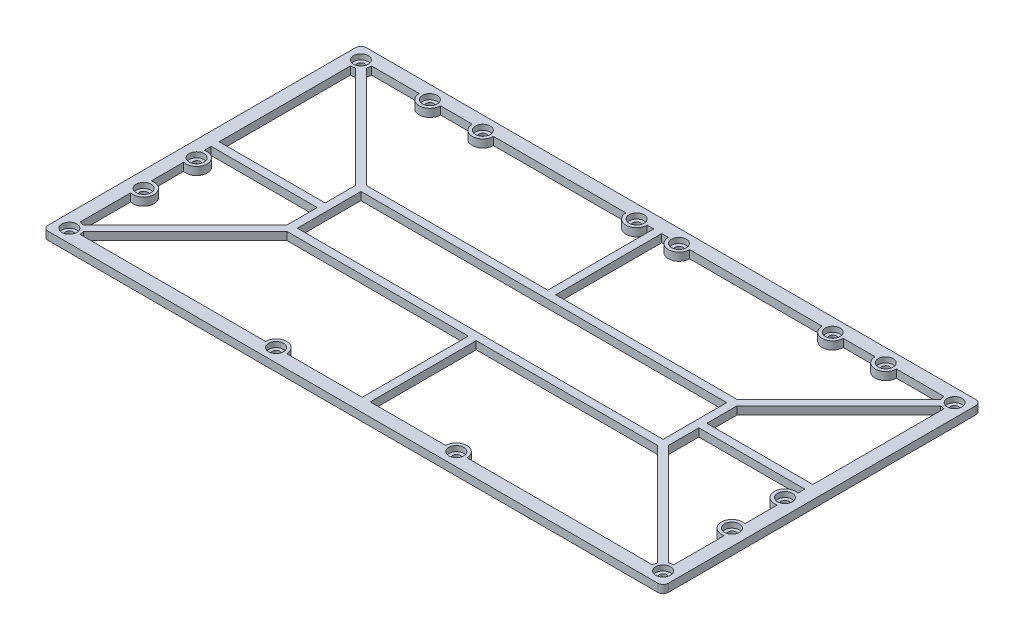
SolidWorks part; units mm, degrees
ref_plane "前视基准面" through (0, 0, 0) normal (0, 0, 1) x (1, 0, 0)
ref_plane "上视基准面" through (0, 0, 0) normal (0, 1, 0) x (1, 0, 0)
ref_plane "右视基准面" through (0, 0, 0) normal (1, 0, 0) x (0, 0, -1)
sketch "草图1" plane through (0, 0, 0) normal (0, 1, 0) x (1, 0, 0)
  line L0 (-13.5, 0) -> (0, 0) construction
  line L1 (-117, 60) -> (117, 60)
  line L2 (-117, 60) -> (-117, -60)
  line L3 (-117, -60) -> (117, -60)
  line L4 (117, 60) -> (117, -60)
  line L5 (-117, 60) -> (117, -60) construction
  line L6 (-117, -60) -> (117, 60) construction
  line L7 (0, 0) -> (0, 78.7988) construction
  circle A0 centre (-58.5, 0) radius 45
  circle A1 centre (58.5, 0) radius 45
  point P0 (0, 0)
  dimension "D3" = 90
  dimension "D4" = 13.5
  dimension "D1" = 234
  dimension "D2" = 120
extrude "凸台-拉伸1" add sketch "草图1" along normal blind 3
sketch "草图2" plane through (0, 3, 0) normal (0, 1, 0) x (1, 0, 0)
  line L0 (-58.5, 0) -> (-58.5, 18.4943) construction
  line L1 (0, 0) -> (0, 13.9098) construction
  circle A8 centre (-58.5, 0) radius 50 construction
  circle A9 centre (-88.5, -40) radius 1.5
  circle A10 centre (-83.5, 43.3013) radius 1.5
  circle A11 centre (-33.5, 43.3013) radius 1.5
  circle A12 centre (-28.5, -40) radius 1.5
  circle A13 centre (28.5, -40) radius 1.5
  circle A14 centre (88.5, -40) radius 1.5
  circle A15 centre (33.5, 43.3013) radius 1.5
  circle A16 centre (83.5, 43.3013) radius 1.5
  dimension "D1" = 100
  dimension "D3" = 30
  dimension "D2" = 3
  dimension "D4" = 25
  dimension "D5" = 3
extrude "切除-拉伸1" cut sketch "草图2" against normal blind 3
sketch "草图3" plane through (0, 3, 0) normal (0, 1, 0) x (1, 0, 0)
  line L0 (-117, 60) -> (-117, -60) construction
  line L1 (-117, -60) -> (117, -60) construction
  line L2 (0, 0) -> (0, -72.8657) construction
  line L3 (117, 60) -> (-117, 60) construction
  circle A0 centre (-111, -28) radius 1.5
  circle A1 centre (-111, -8) radius 1.5
  circle A2 centre (111, -8) radius 1.5
  circle A3 centre (111, -28) radius 1.5
  circle A4 centre (-86, 55) radius 1.5
  circle A5 centre (-66, 55) radius 1.5
  circle A6 centre (66, 55) radius 1.5
  circle A7 centre (86, 55) radius 1.5
  dimension "D1" = 3
  dimension "D2" = 6
  dimension "D3" = 32
  dimension "D4" = 3
  dimension "D5" = 20
  dimension "D6" = 3
  dimension "D7" = 5
  dimension "D8" = 31
  dimension "D9" = 3
  dimension "D10" = 20
extrude "切除-拉伸2" cut sketch "草图3" against normal blind 3
sketch "草图4" plane through (0, 3, 0) normal (0, 1, 0) x (1, 0, 0)
  line L0 (-117, 60) -> (-117, -60) construction
  line L1 (-117, -60) -> (117, -60) construction
  line L2 (117, 60) -> (-117, 60) construction
  line L3 (117, -60) -> (117, 60) construction
  circle A0 centre (-112, -55) radius 1.5
  circle A1 centre (-112, 55) radius 1.5
  circle A2 centre (112, 55) radius 1.5
  circle A3 centre (112, -55) radius 1.5
  circle A4 centre (-34, -55) radius 1.5
  circle A5 centre (34, -55) radius 1.5
  dimension "D1" = 3
  dimension "D2" = 5
  dimension "D3" = 5
  dimension "D4" = 3
  dimension "D5" = 5
  dimension "D6" = 5
  dimension "D7" = 3
  dimension "D8" = 5
  dimension "D9" = 5
  dimension "D10" = 3
  dimension "D11" = 3
  dimension "D12" = 78
  dimension "D13" = 3
  dimension "D14" = 78
  dimension "D15" = 5
  dimension "D16" = 5
  dimension "D17" = 5
  dimension "D18" = 5
extrude "切除-拉伸3" cut sketch "草图4" against normal blind 3
sketch "草图5" plane through (0, 3, 0) normal (0, 1, 0) x (1, 0, 0)
  line L0 (117, 60) -> (-117, 60) construction
  circle A0 centre (-8, 55) radius 1.5
  circle A1 centre (8, 55) radius 1.5
  dimension "D1" = 3
  dimension "D2" = 5
  dimension "D3" = 8
  dimension "D4" = 3
  dimension "D5" = 5
  dimension "D6" = 8
extrude "切除-拉伸4" cut sketch "草图5" against normal blind 3
fillet "圆角1" radius 2 4 edges at (-117, 1.5, -60) (-117, 1.5, 60) (117, 1.5, 60) (117, 1.5, -60)
sketch "草图6" plane through (0, 3, 0) normal (0, 1, 0) x (1, 0, 0)
  line L5 (109.5, -12.7697) -> (109.5, -23.2303)
  line L6 (-107.6699, 52.5) -> (-90.3301, 52.5)
  line L7 (-109.5, 50.6699) -> (-109.5, -3.2303)
  line L12 (-107.6699, -52.5) -> (-38.3301, -52.5)
  line L13 (109.5, 50.6699) -> (109.5, -3.2303)
  line L14 (-108.1247, 51.8406) -> (108.1247, -51.8406) construction
  line L15 (-108.1247, -51.8406) -> (108.1247, 51.8406) construction
  line L16 (109.5, -32.7697) -> (109.5, -50.6699)
  line L17 (90.3301, 52.5) -> (107.6699, 52.5)
  line L18 (70.3301, 52.5) -> (81.6699, 52.5)
  line L19 (12.3301, 52.5) -> (61.6699, 52.5)
  line L20 (-3.6699, 52.5) -> (3.6699, 52.5)
  line L21 (-81.6699, 52.5) -> (-70.3301, 52.5)
  line L22 (-61.6699, 52.5) -> (-12.3301, 52.5)
  line L23 (-109.5, -12.7697) -> (-109.5, -23.2303)
  line L24 (-109.5, -32.7697) -> (-109.5, -50.6699)
  line L25 (-29.6699, -52.5) -> (29.6699, -52.5)
  line L26 (38.3301, -52.5) -> (107.6699, -52.5)
  arc A12 (-109.5, -12.7697) -> (-109.5, -3.2303) centre (-111, -8) ccw
  arc A13 (-109.5, -32.7697) -> (-109.5, -23.2303) centre (-111, -28) ccw
  arc A14 (-109.5, 50.6699) -> (-107.6699, 52.5) centre (-112, 55) ccw
  arc A15 (-90.3301, 52.5) -> (-81.6699, 52.5) centre (-86, 55) ccw
  arc A16 (-70.3301, 52.5) -> (-61.6699, 52.5) centre (-66, 55) ccw
  arc A17 (-12.3301, 52.5) -> (-3.6699, 52.5) centre (-8, 55) ccw
  arc A18 (3.6699, 52.5) -> (12.3301, 52.5) centre (8, 55) ccw
  arc A19 (61.6699, 52.5) -> (70.3301, 52.5) centre (66, 55) ccw
  arc A20 (81.6699, 52.5) -> (90.3301, 52.5) centre (86, 55) ccw
  arc A21 (107.6699, 52.5) -> (109.5, 50.6699) centre (112, 55) ccw
  arc A22 (109.5, -3.2303) -> (109.5, -12.7697) centre (111, -8) ccw
  arc A23 (109.5, -23.2303) -> (109.5, -32.7697) centre (111, -28) ccw
  arc A24 (109.5, -50.6699) -> (107.6699, -52.5) centre (112, -55) ccw
  arc A25 (38.3301, -52.5) -> (29.6699, -52.5) centre (34, -55) ccw
  arc A26 (-29.6699, -52.5) -> (-38.3301, -52.5) centre (-34, -55) ccw
  arc A27 (-107.6699, -52.5) -> (-109.5, -50.6699) centre (-112, -55) ccw
  point P0 (0, 0)
  dimension "D3" = 10
  dimension "D4" = 10
  dimension "D5" = 10
  dimension "D6" = 10
  dimension "D7" = 10
  dimension "D8" = 10
  dimension "D9" = 10
  dimension "D10" = 10
  dimension "D11" = 10
  dimension "D12" = 10
  dimension "D13" = 10
  dimension "D14" = 10
  dimension "D15" = 10
  dimension "D16" = 10
  dimension "D17" = 10
  dimension "D18" = 10
extrude "切除-拉伸5" cut sketch "草图6" against normal blind 10
sketch "草图7" plane through (0, 3, 0) normal (0, 1, 0) x (1, 0, 0)
  line L0 (-90.3301, 52.5) -> (-107.6699, 52.5) construction
  line L1 (-70.3301, 52.5) -> (-81.6699, 52.5) construction
  line L2 (-12.3301, 52.5) -> (-61.6699, 52.5) construction
  line L3 (-109.5, 50.6699) -> (-109.5, -3.2303) construction
  line L4 (-117, 58) -> (-117, -58)
  line L5 (-115, -60) -> (115, -60)
  line L6 (117, -58) -> (117, 58)
  line L7 (115, 60) -> (-115, 60)
  line L8 (-117, 58) -> (-117, -58)
  line L9 (-115, -60) -> (115, -60)
  line L10 (117, -58) -> (117, 58)
  line L11 (115, 60) -> (-115, 60)
  line L12 (-109.5, -12.7697) -> (-109.5, -23.2303) construction
  line L13 (-109.5, -32.7697) -> (-109.5, -50.6699) construction
  line L14 (-107.6699, -52.5) -> (-38.3301, -52.5) construction
  line L15 (-29.6699, -52.5) -> (29.6699, -52.5) construction
  line L16 (38.3301, -52.5) -> (107.6699, -52.5) construction
  line L17 (3.6699, 52.5) -> (-3.6699, 52.5) construction
  line L18 (61.6699, 52.5) -> (12.3301, 52.5) construction
  line L19 (81.6699, 52.5) -> (70.3301, 52.5) construction
  line L20 (107.6699, 52.5) -> (90.3301, 52.5) construction
  line L21 (109.5, -3.2303) -> (109.5, 50.6699) construction
  line L22 (109.5, -23.2303) -> (109.5, -12.7697) construction
  line L23 (109.5, -50.6699) -> (109.5, -32.7697) construction
  line L24 (109.5, -50.6699) -> (109.5, -32.7697)
  line L25 (109.5, -23.2303) -> (109.5, -12.7697)
  line L26 (109.5, -3.2303) -> (109.5, 50.6699)
  line L27 (107.6699, 52.5) -> (90.3301, 52.5)
  line L28 (81.6699, 52.5) -> (70.3301, 52.5)
  line L29 (61.6699, 52.5) -> (12.3301, 52.5)
  line L30 (3.6699, 52.5) -> (-3.6699, 52.5)
  line L31 (38.3301, -52.5) -> (107.6699, -52.5)
  line L32 (-29.6699, -52.5) -> (29.6699, -52.5)
  line L33 (-107.6699, -52.5) -> (-38.3301, -52.5)
  line L34 (-109.5, -32.7697) -> (-109.5, -50.6699)
  line L35 (-109.5, -12.7697) -> (-109.5, -23.2303)
  line L36 (-109.5, 50.6699) -> (-109.5, -3.2303)
  line L37 (-12.3301, 52.5) -> (-61.6699, 52.5)
  line L38 (-70.3301, 52.5) -> (-81.6699, 52.5)
  line L39 (-90.3301, 52.5) -> (-107.6699, 52.5)
  circle A0 centre (-112, 55) radius 1.5 construction
  circle A1 centre (-111, -8) radius 1.5 construction
  circle A2 centre (-111, -28) radius 1.5 construction
  circle A3 centre (-112, -55) radius 1.5 construction
  arc A4 (-117, -58) -> (-115, -60) centre (-115, -58) ccw
  arc A5 (115, -60) -> (117, -58) centre (115, -58) ccw
  arc A6 (117, 58) -> (115, 60) centre (115, 58) ccw
  arc A7 (-115, 60) -> (-117, 58) centre (-115, 58) ccw
  arc A8 (-117, -58) -> (-115, -60) centre (-115, -58) ccw
  arc A9 (115, -60) -> (117, -58) centre (115, -58) ccw
  arc A10 (117, 58) -> (115, 60) centre (115, 58) ccw
  arc A11 (-115, 60) -> (-117, 58) centre (-115, 58) ccw
  arc A12 (-109.5, 50.6699) -> (-107.6699, 52.5) centre (-112, 55) ccw construction
  arc A13 (-90.3301, 52.5) -> (-81.6699, 52.5) centre (-86, 55) ccw construction
  circle A14 centre (-86, 55) radius 1.5 construction
  circle A15 centre (-66, 55) radius 1.5 construction
  circle A16 centre (-8, 55) radius 1.5 construction
  circle A17 centre (8, 55) radius 1.5 construction
  circle A18 centre (66, 55) radius 1.5 construction
  circle A19 centre (86, 55) radius 1.5 construction
  arc A20 (-70.3301, 52.5) -> (-61.6699, 52.5) centre (-66, 55) ccw construction
  arc A21 (-109.5, -12.7697) -> (-109.5, -3.2303) centre (-111, -8) ccw construction
  arc A22 (-109.5, -32.7697) -> (-109.5, -23.2303) centre (-111, -28) ccw construction
  arc A23 (-107.6699, -52.5) -> (-109.5, -50.6699) centre (-112, -55) ccw construction
  circle A24 centre (-34, -55) radius 1.5 construction
  arc A25 (-29.6699, -52.5) -> (-38.3301, -52.5) centre (-34, -55) ccw construction
  arc A26 (38.3301, -52.5) -> (29.6699, -52.5) centre (34, -55) ccw construction
  circle A27 centre (34, -55) radius 1.5 construction
  arc A28 (-12.3301, 52.5) -> (-3.6699, 52.5) centre (-8, 55) ccw construction
  arc A29 (3.6699, 52.5) -> (12.3301, 52.5) centre (8, 55) ccw construction
  arc A30 (61.6699, 52.5) -> (70.3301, 52.5) centre (66, 55) ccw construction
  arc A31 (81.6699, 52.5) -> (90.3301, 52.5) centre (86, 55) ccw construction
  arc A32 (107.6699, 52.5) -> (109.5, 50.6699) centre (112, 55) ccw construction
  circle A33 centre (112, 55) radius 1.5 construction
  arc A34 (109.5, -3.2303) -> (109.5, -12.7697) centre (111, -8) ccw construction
  circle A35 centre (111, -8) radius 1.5 construction
  arc A36 (109.5, -23.2303) -> (109.5, -32.7697) centre (111, -28) ccw construction
  circle A37 centre (111, -28) radius 1.5 construction
  arc A38 (109.5, -50.6699) -> (107.6699, -52.5) centre (112, -55) ccw construction
  circle A39 centre (112, -55) radius 1.5 construction
  circle A40 centre (112, -55) radius 1.5
  arc A41 (109.5, -50.6699) -> (107.6699, -52.5) centre (112, -55) ccw
  circle A42 centre (111, -28) radius 1.5
  arc A43 (109.5, -23.2303) -> (109.5, -32.7697) centre (111, -28) ccw
  circle A44 centre (111, -8) radius 1.5
  arc A45 (109.5, -3.2303) -> (109.5, -12.7697) centre (111, -8) ccw
  circle A46 centre (112, 55) radius 1.5
  arc A47 (107.6699, 52.5) -> (109.5, 50.6699) centre (112, 55) ccw
  arc A48 (81.6699, 52.5) -> (90.3301, 52.5) centre (86, 55) ccw
  arc A49 (61.6699, 52.5) -> (70.3301, 52.5) centre (66, 55) ccw
  arc A50 (3.6699, 52.5) -> (12.3301, 52.5) centre (8, 55) ccw
  arc A51 (-12.3301, 52.5) -> (-3.6699, 52.5) centre (-8, 55) ccw
  circle A52 centre (34, -55) radius 1.5
  arc A53 (38.3301, -52.5) -> (29.6699, -52.5) centre (34, -55) ccw
  arc A54 (-29.6699, -52.5) -> (-38.3301, -52.5) centre (-34, -55) ccw
  circle A55 centre (-34, -55) radius 1.5
  arc A56 (-107.6699, -52.5) -> (-109.5, -50.6699) centre (-112, -55) ccw
  arc A57 (-109.5, -32.7697) -> (-109.5, -23.2303) centre (-111, -28) ccw
  arc A58 (-109.5, -12.7697) -> (-109.5, -3.2303) centre (-111, -8) ccw
  arc A59 (-70.3301, 52.5) -> (-61.6699, 52.5) centre (-66, 55) ccw
  circle A60 centre (86, 55) radius 1.5
  circle A61 centre (66, 55) radius 1.5
  circle A62 centre (8, 55) radius 1.5
  circle A63 centre (-8, 55) radius 1.5
  circle A64 centre (-66, 55) radius 1.5
  circle A65 centre (-86, 55) radius 1.5
  arc A66 (-90.3301, 52.5) -> (-81.6699, 52.5) centre (-86, 55) ccw
  arc A67 (-109.5, 50.6699) -> (-107.6699, 52.5) centre (-112, 55) ccw
  circle A68 centre (-112, 55) radius 1.5
  circle A69 centre (-112, -55) radius 1.5
  circle A70 centre (-111, -28) radius 1.5
  circle A71 centre (-111, -8) radius 1.5
  dimension "D1" = 0
extrude "凸台-拉伸2" add sketch "草图7" along normal blind 17
sketch "草图8" plane through (0, 20, 0) normal (0, 1, 0) x (1, 0, 0)
  line L0 (-90, 55) -> (-108, 55)
  line L1 (108, -55) -> (38, -55)
  line L2 (112, -51) -> (112, -31.873)
  line L3 (108, 55) -> (90, 55)
  line L4 (-112, -51) -> (-112, -31.873)
  line L5 (108.4096, -53.2368) -> (-108.4096, 53.2368) construction
  line L6 (108.4096, 53.2368) -> (-108.4096, -53.2368) construction
  line L7 (-70, 55) -> (-82, 55)
  line L8 (-12, 55) -> (-62, 55)
  line L9 (4, 55) -> (-4, 55)
  line L10 (62, 55) -> (12, 55)
  line L11 (82, 55) -> (70, 55)
  line L12 (112, -4.127) -> (112, 51)
  line L13 (112, -24.127) -> (112, -11.873)
  line L14 (30, -55) -> (-30, -55)
  line L15 (-38, -55) -> (-108, -55)
  line L16 (-112, -24.127) -> (-112, -11.873)
  line L17 (-112, -4.127) -> (-112, 51)
  arc A0 (-112, -11.873) -> (-112, -4.127) centre (-111, -8) ccw
  arc A1 (-112, -31.873) -> (-112, -24.127) centre (-111, -28) ccw
  arc A2 (-108, -55) -> (-112, -51) centre (-112, -55) ccw
  arc A3 (-30, -55) -> (-38, -55) centre (-34, -55) ccw
  arc A4 (-112, 51) -> (-108, 55) centre (-112, 55) ccw
  arc A5 (-90, 55) -> (-82, 55) centre (-86, 55) ccw
  arc A6 (-70, 55) -> (-62, 55) centre (-66, 55) ccw
  arc A7 (-12, 55) -> (-4, 55) centre (-8, 55) ccw
  arc A8 (4, 55) -> (12, 55) centre (8, 55) ccw
  arc A9 (62, 55) -> (70, 55) centre (66, 55) ccw
  arc A10 (82, 55) -> (90, 55) centre (86, 55) ccw
  arc A11 (108, 55) -> (112, 51) centre (112, 55) ccw
  arc A12 (112, -4.127) -> (112, -11.873) centre (111, -8) ccw
  arc A13 (112, -24.127) -> (112, -31.873) centre (111, -28) ccw
  arc A14 (112, -51) -> (108, -55) centre (112, -55) ccw
  arc A15 (38, -55) -> (30, -55) centre (34, -55) ccw
  point P48 (0, 0)
  dimension "D1" = 8
  dimension "D2" = 8
  dimension "D3" = 8
  dimension "D4" = 8
  dimension "D5" = 8
  dimension "D6" = 8
  dimension "D7" = 8
  dimension "D8" = 8
  dimension "D9" = 8
  dimension "D10" = 8
  dimension "D11" = 8
  dimension "D12" = 8
  dimension "D13" = 8
  dimension "D14" = 8
  dimension "D15" = 8
  dimension "D16" = 8
extrude "切除-拉伸6" cut sketch "草图8" against normal blind 50
sketch "草图9" plane through (0, 20, 0) normal (0, 1, 0) x (1, 0, 0)
  line L0 (0, 0) -> (-6.4511, 0) construction
  line L1 (-117, 60) -> (117, 60)
  line L2 (-117, 60) -> (-117, -60)
  line L3 (-117, -60) -> (117, -60)
  line L4 (117, 60) -> (117, -60)
  line L5 (-117, 60) -> (117, -60) construction
  line L6 (-117, -60) -> (117, 60) construction
  line L7 (69.8787, -15) -> (108.3173, -53.4386)
  line L8 (-69, 12) -> (-69, -12)
  line L9 (-69, -12) -> (69, -12)
  line L10 (69, 12) -> (69, -12)
  line L11 (-69, 12) -> (69, 12)
  line L12 (-72, 12.8787) -> (-72, 1.5)
  line L13 (-69.8787, -15) -> (-1.5, -15)
  line L14 (72, 12.8787) -> (72, 1.5)
  line L15 (-69.8787, 15) -> (-1.5, 15)
  line L16 (72, 1.5) -> (112, 1.5)
  line L17 (112, -4.127) -> (112, 51) construction
  line L18 (72, -1.5) -> (112, -1.5)
  line L19 (72, -1.5) -> (72, -12.8787)
  line L20 (0, 0) -> (0, 9.3049) construction
  line L21 (69.8787, 15) -> (108.3173, 53.4386)
  line L22 (112, 55) -> (109.1716, 52.1716) construction
  line L23 (72, 12.8787) -> (110.4386, 51.3173)
  line L24 (72, -12.8787) -> (110.4386, -51.3173)
  line L25 (-1.5, 55) -> (-1.5, 15)
  line L26 (4, 55) -> (-4, 55) construction
  line L27 (1.5, 55) -> (1.5, 15)
  line L28 (1.5, 15) -> (69.8787, 15)
  line L29 (-112, 55) -> (-109.1716, 52.1716) construction
  line L30 (-72, -12.8787) -> (-110.4386, -51.3173)
  line L31 (-72, 12.8787) -> (-110.4386, 51.3173)
  line L32 (-69.8787, 15) -> (-108.3173, 53.4386)
  line L33 (-72, -1.5) -> (-72, -12.8787)
  line L34 (-72, -1.5) -> (-112, -1.5)
  line L35 (-72, 1.5) -> (-112, 1.5)
  line L36 (-72, 12.8787) -> (-72, 1.5)
  line L37 (-69, 12) -> (-69, -12)
  line L38 (-69.8787, -15) -> (-108.3173, -53.4386)
  line L39 (-117, 60) -> (-117, -60)
  line L40 (-72, -1.5) -> (-72, -12.8787)
  line L41 (1.5, -55) -> (1.5, -15)
  line L42 (-1.5, -55) -> (-1.5, -15)
  line L43 (1.5, -15) -> (69.8787, -15)
  line L44 (-30, -55) -> (30, -55) construction
  line L45 (-108, -55) -> (-38, -55) construction
  line L46 (38, -55) -> (108, -55) construction
  line L47 (112, -51) -> (112, -31.873) construction
  line L48 (112, -24.127) -> (112, -11.873) construction
  line L49 (108, 55) -> (90, 55) construction
  line L50 (82, 55) -> (70, 55) construction
  line L51 (62, 55) -> (12, 55) construction
  line L52 (-12, 55) -> (-62, 55) construction
  line L53 (-70, 55) -> (-82, 55) construction
  line L54 (-90, 55) -> (-108, 55) construction
  line L55 (-112, 51) -> (-112, -4.127) construction
  line L56 (-112, -11.873) -> (-112, -24.127) construction
  line L57 (-112, -31.873) -> (-112, -51) construction
  line L58 (-112, -31.873) -> (-112, -51)
  line L59 (-112, -11.873) -> (-112, -24.127)
  line L60 (-112, 51) -> (-112, 1.5)
  line L61 (-90, 55) -> (-108, 55)
  line L62 (-70, 55) -> (-82, 55)
  line L63 (-12, 55) -> (-62, 55)
  line L64 (4, 55) -> (1.5, 55)
  line L65 (62, 55) -> (12, 55)
  line L66 (82, 55) -> (70, 55)
  line L67 (108, 55) -> (90, 55)
  line L68 (112, -4.127) -> (112, -1.5)
  line L69 (112, -24.127) -> (112, -11.873)
  line L70 (112, -51) -> (112, -31.873)
  line L71 (38, -55) -> (108, -55)
  line L72 (-108, -55) -> (-38, -55)
  line L73 (-30, -55) -> (-1.5, -55)
  line L74 (1.5, -55) -> (30, -55)
  line L75 (-112, -1.5) -> (-112, -4.127)
  line L76 (-1.5, 55) -> (-4, 55)
  line L77 (112, 1.5) -> (112, 51)
  arc A0 (-30, -55) -> (-38, -55) centre (-34, -55) ccw construction
  arc A1 (108, 55) -> (112, 51) centre (112, 55) ccw construction
  circle A2 centre (-34, -55) radius 1.5 construction
  arc A3 (38, -55) -> (30, -55) centre (34, -55) ccw construction
  circle A4 centre (34, -55) radius 1.5 construction
  arc A5 (112, -51) -> (108, -55) centre (112, -55) ccw construction
  circle A6 centre (112, -55) radius 1.5 construction
  arc A7 (112, -24.127) -> (112, -31.873) centre (111, -28) ccw construction
  circle A8 centre (111, -28) radius 1.5 construction
  arc A9 (112, -4.127) -> (112, -11.873) centre (111, -8) ccw construction
  circle A10 centre (111, -8) radius 1.5 construction
  circle A11 centre (112, 55) radius 1.5 construction
  arc A12 (82, 55) -> (90, 55) centre (86, 55) ccw construction
  circle A13 centre (86, 55) radius 1.5 construction
  circle A14 centre (66, 55) radius 1.5 construction
  arc A15 (62, 55) -> (70, 55) centre (66, 55) ccw construction
  circle A16 centre (8, 55) radius 1.5 construction
  arc A17 (4, 55) -> (12, 55) centre (8, 55) ccw construction
  arc A18 (-12, 55) -> (-4, 55) centre (-8, 55) ccw construction
  circle A19 centre (-8, 55) radius 1.5 construction
  circle A20 centre (-86, 55) radius 1.5 construction
  arc A21 (-90, 55) -> (-82, 55) centre (-86, 55) ccw construction
  circle A22 centre (-66, 55) radius 1.5 construction
  arc A23 (-70, 55) -> (-62, 55) centre (-66, 55) ccw construction
  circle A24 centre (-112, 55) radius 1.5 construction
  arc A25 (-112, 51) -> (-108, 55) centre (-112, 55) ccw construction
  arc A26 (-112, -11.873) -> (-112, -4.127) centre (-111, -8) ccw construction
  circle A27 centre (-111, -8) radius 1.5 construction
  arc A28 (-112, -31.873) -> (-112, -24.127) centre (-111, -28) ccw construction
  circle A29 centre (-111, -28) radius 1.5 construction
  arc A30 (-108, -55) -> (-112, -51) centre (-112, -55) ccw construction
  circle A31 centre (-112, -55) radius 1.5 construction
  circle A32 centre (-112, -55) radius 1.5
  arc A33 (-108, -55) -> (-108.3173, -53.4386) centre (-112, -55) ccw
  circle A34 centre (-111, -28) radius 1.5
  arc A35 (-112, -31.873) -> (-112, -24.127) centre (-111, -28) ccw
  circle A36 centre (-111, -8) radius 1.5
  arc A37 (-112, -11.873) -> (-112, -4.127) centre (-111, -8) ccw
  arc A38 (-112, 51) -> (-110.4386, 51.3173) centre (-112, 55) ccw
  circle A39 centre (-112, 55) radius 1.5
  arc A40 (-70, 55) -> (-62, 55) centre (-66, 55) ccw
  circle A41 centre (-66, 55) radius 1.5
  arc A42 (-90, 55) -> (-82, 55) centre (-86, 55) ccw
  circle A43 centre (-86, 55) radius 1.5
  circle A44 centre (-8, 55) radius 1.5
  arc A45 (-12, 55) -> (-4, 55) centre (-8, 55) ccw
  arc A46 (4, 55) -> (12, 55) centre (8, 55) ccw
  circle A47 centre (8, 55) radius 1.5
  arc A48 (62, 55) -> (70, 55) centre (66, 55) ccw
  circle A49 centre (66, 55) radius 1.5
  circle A50 centre (86, 55) radius 1.5
  arc A51 (82, 55) -> (90, 55) centre (86, 55) ccw
  arc A52 (108, 55) -> (108.3173, 53.4386) centre (112, 55) ccw
  circle A53 centre (112, 55) radius 1.5
  circle A54 centre (111, -8) radius 1.5
  arc A55 (112, -4.127) -> (112, -11.873) centre (111, -8) ccw
  circle A56 centre (111, -28) radius 1.5
  arc A57 (112, -24.127) -> (112, -31.873) centre (111, -28) ccw
  circle A58 centre (112, -55) radius 1.5
  arc A59 (112, -51) -> (110.4386, -51.3173) centre (112, -55) ccw
  circle A60 centre (34, -55) radius 1.5
  arc A61 (38, -55) -> (30, -55) centre (34, -55) ccw
  circle A62 centre (-34, -55) radius 1.5
  arc A63 (-30, -55) -> (-38, -55) centre (-34, -55) ccw
  arc A64 (-110.4386, -51.3173) -> (-112, -51) centre (-112, -55) ccw
  arc A65 (-108.3173, 53.4386) -> (-108, 55) centre (-112, 55) ccw
  arc A66 (110.4386, 51.3173) -> (112, 51) centre (112, 55) ccw
  arc A67 (108.3173, -53.4386) -> (108, -55) centre (112, -55) ccw
  point P0 (0, 0)
  dimension "D1" = 120
  dimension "D2" = 234
  dimension "D5" = 1.5
  dimension "D6" = 3
  dimension "D7" = 1.5
  dimension "D3" = 3
extrude "凸台-拉伸3" add sketch "草图9" along normal blind 3 from offset 20 separate body contours L4 L1 L2 L3 A62 A60 A58 A56 A54 A53 A50 A49 A47 A44 A43 A41 A39 A36 A34 A32 L8 L11 L10 L9 L60 A38 L31 L12 L35 L67 A52 L21
sketch "草图10" plane through (0, 20, 0) normal (0, 1, 0) x (1, 0, 0)
  line L1 (-194.2109, 108.9542) -> (194.2109, 108.9542)
  line L2 (-194.2109, 108.9542) -> (-194.2109, -108.9542)
  line L3 (-194.2109, -108.9542) -> (194.2109, -108.9542)
  line L4 (194.2109, 108.9542) -> (194.2109, -108.9542)
  line L5 (-194.2109, 108.9542) -> (194.2109, -108.9542) construction
  line L6 (-194.2109, -108.9542) -> (194.2109, 108.9542) construction
  point P0 (0, 0)
extrude "切除-拉伸7" cut sketch "草图10" against normal blind 90
fillet "圆角2" radius 2 4 edges at (117, 41.5, 60) (117, 41.5, -60) (-117, 41.5, -60) (-117, 41.5, 60)
sketch "草图11" plane through (0, 43, 0) normal (0, 1, 0) x (1, 0, 0)
  circle A0 centre (-112, 55) radius 2.8
  circle A1 centre (-86, 55) radius 2.8
  circle A2 centre (-66, 55) radius 2.8
  circle A3 centre (-111, -8) radius 2.8
  circle A4 centre (-111, -28) radius 2.8
  circle A5 centre (-112, -55) radius 2.8
  circle A6 centre (-34, -55) radius 2.8
  circle A7 centre (34, -55) radius 2.8
  circle A8 centre (112, -55) radius 2.8
  circle A9 centre (-8, 55) radius 2.8
  circle A10 centre (8, 55) radius 2.8
  circle A11 centre (66, 55) radius 2.8
  circle A12 centre (86, 55) radius 2.8
  circle A13 centre (112, 55) radius 2.8
  circle A14 centre (111, -8) radius 2.8
  circle A15 centre (111, -28) radius 2.8
  dimension "D1" = 5.6
  dimension "D2" = 5.6
  dimension "D3" = 5.6
  dimension "D4" = 5.6
  dimension "D5" = 5.6
  dimension "D6" = 5.6
  dimension "D7" = 5.6
  dimension "D8" = 5.6
  dimension "D9" = 5.6
  dimension "D10" = 5.6
  dimension "D11" = 5.6
  dimension "D12" = 5.6
  dimension "D13" = 5.6
  dimension "D14" = 5.6
  dimension "D15" = 5.6
  dimension "D16" = 5.6
extrude "切除-拉伸8" cut sketch "草图11" against normal blind 2
